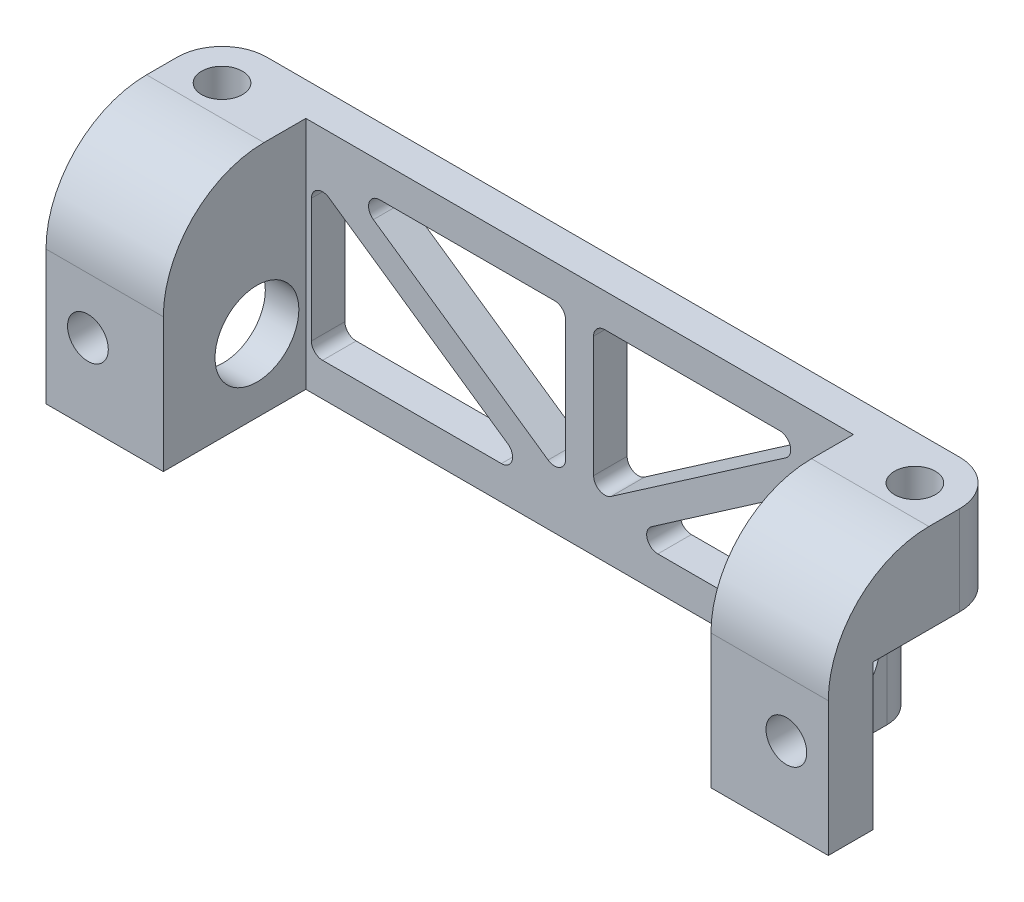
SolidWorks part; units mm, degrees
ref_plane "Front Plane" through (0, 0, 0) normal (0, 0, 1) x (1, 0, 0)
ref_plane "Top Plane" through (0, 0, 0) normal (0, 1, 0) x (1, 0, 0)
ref_plane "Right Plane" through (0, 0, 0) normal (1, 0, 0) x (0, 0, -1)
sketch "Sketch1" plane through (0, 0, 0) normal (0, 1, 0) x (1, 0, 0)
  line L0 (0, -12.75) -> (0, 12.75) construction
  line L1 (-24.5, -12.75) -> (24.5, -12.75)
  line L2 (-24.5, -12.75) -> (-24.5, 12.75)
  line L3 (-24.5, 12.75) -> (24.5, 12.75)
  line L4 (24.5, -12.75) -> (24.5, 12.75)
  line L5 (-24.5, -12.75) -> (24.5, 12.75) construction
  line L6 (-24.5, 12.75) -> (24.5, -12.75) construction
  line L7 (0, 12.75) -> (0, 15.75)
  line L9 (0, 15.75) -> (-27.5, 15.75)
  line L10 (0, 15.75) -> (0, 12.75)
  line L11 (0, 12.75) -> (-27.5, 12.75)
  line L12 (-27.5, 15.75) -> (-27.5, 12.75)
  line L13 (-24.5, 12.75) -> (-27.5, 12.75)
  line L14 (-24.5, 12.75) -> (-24.5, 0)
  line L15 (-24.5, 0) -> (-27.5, 0)
  line L16 (-27.5, 12.75) -> (-27.5, 0)
  line L17 (-27.5, 0) -> (-35, 0)
  line L18 (-27.5, 0) -> (-27.5, 3)
  line L19 (-27.5, 3) -> (-35, 3)
  line L20 (-35, 0) -> (-35, 3)
  line L21 (-35, 3) -> (-27.5, 3)
  line L22 (-35, 3) -> (-35, 15.75)
  line L23 (-35, 15.75) -> (-27.5, 15.75)
  line L24 (-27.5, 3) -> (-27.5, 15.75)
  point P0 (0, 0)
  dimension "D1" = 49
  dimension "D2" = 25.5
  dimension "D3" = 3
  dimension "D4" = 27.5
  dimension "D5" = 12.75
  dimension "D6" = 7.5
  dimension "D7" = 3
extrude "Boss-Extrude1" add sketch "Sketch1" along normal blind 21
sketch "Sketch2" plane through (0, 0, 0) normal (0, 0, 1) x (1, 0, 0)
  line L0 (-27.5, 0) -> (-27.5, 21) construction
  line L1 (-24.5, 0) -> (-35, 0) construction
  line L2 (-24.5, 21) -> (-35, 21) construction
  line L3 (-24.5, 21) -> (-24.5, 0) construction
  line L4 (-27.5, 14) -> (-35, 14)
  line L5 (-35, 21) -> (-35, 0) construction
  line L6 (-35, 14) -> (-27.5, 0) construction
  line L7 (-27.5, 0) -> (-35, 0) construction
  line L8 (-35, 0) -> (-27.5, 14) construction
  circle A0 centre (-31.25, 7) radius 1.825
  dimension "D3" = 3.65
  dimension "D1" = 3
  dimension "D2" = 7
extrude "Cut-Extrude1" cut sketch "Sketch2" against normal blind 4 contours A0
sketch "Sketch3" plane through (0, 0, 0) normal (0, -1, 0) x (1, 0, 0)
  line L0 (-24.5, 0) -> (-24.5, -12.75) construction
  line L1 (-35, -15.75) -> (-27.5, -15.75)
  line L2 (-35, -15.75) -> (-35, -4)
  line L3 (-35, -4) -> (-27.5, -4)
  line L4 (-27.5, -15.75) -> (-27.5, -4)
  line L5 (-24.5, 0) -> (-35, 0) construction
  dimension "D1" = 3
  dimension "D2" = 4
extrude "Cut-Extrude2" cut sketch "Sketch3" against normal blind 13
fillet "Fillet1" radius 4 1 edges at (-35, 17, -15.75)
sketch "Sketch5" plane through (0, 13, 0) normal (0, -1, 0) x (1, 0, 0)
  line L0 (-35, -11.75) -> (-27.5, -11.75) construction
  line L1 (-27.5, -15.75) -> (-27.5, -4) construction
  line L2 (-31, -15.75) -> (-31, -4) construction
  line L3 (-27.5, -4) -> (-35, -4) construction
  circle A0 centre (-31, -11.75) radius 1.825
  dimension "D1" = 3.65
extrude "Cut-Extrude3" cut sketch "Sketch5" against normal through all
mirror "Mirror1" about plane through (0, 21, 0) normal (-1, 0, 0) of "Cut-Extrude3", "Fillet1", "Cut-Extrude1", "Cut-Extrude2", "Boss-Extrude1"
ref_plane "Plane1" through (0, 0, -15.75) normal (0, 0, -1) x (-1, 0, 0)
sketch "Sketch10" plane through (0, 0, -15.75) normal (0, 0, -1) x (-1, 0, 0)
  line L0 (-27.5, 0) -> (27.5, 0) construction
  line L1 (-31, 21) -> (31, 21) construction
  line L2 (-27.5, 13) -> (-27.5, 0) construction
  line L3 (-24, 3) -> (-3.7939, 3)
  line L4 (-24, 3) -> (-24, 16.9699)
  line L5 (-21.0939, 18) -> (-1.25, 18)
  line L7 (-21.0939, 18) -> (-1.25, 4.2806)
  line L11 (-1.25, 4.2806) -> (-1.25, 18)
  line L14 (0, 0) -> (0, -5.962) construction
  line L16 (-24, 16.9699) -> (-3.7939, 3)
  line L17 (24, 3) -> (24, 16.9699)
  line L18 (24, 16.9699) -> (3.7939, 3)
  line L19 (24, 3) -> (3.7939, 3)
  line L20 (21.0939, 18) -> (1.25, 4.2806)
  line L21 (21.0939, 18) -> (1.25, 18)
  line L22 (1.25, 4.2806) -> (1.25, 18)
  point P5 (0, 10.5)
  point P6 (-12.5701, 10.5832)
  point P12 (0, 10.5)
  dimension "D1" = 3
  dimension "D2" = 3.5
  dimension "D3" = 4.2806
  dimension "D4" = 3
  dimension "D5" = 2.5
  dimension "D6" = 26.25
  dimension "D7" = 6.4061
extrude "Cut-Extrude5" cut sketch "Sketch10" against normal through all
fillet "Fillet2" radius 1 12 edges at (1.25, 4.2806, -14.25) (-1.25, 4.2806, -14.25) (-1.25, 18, -14.25) (-24, 16.9699, -14.25) (-24, 3, -14.25) (24, 3, -14.25) (24, 16.9699, -14.25) (3.7939, 3, -14.25) (-3.7939, 3, -14.25) (-21.0939, 18, -14.25) (1.25, 18, -14.25) (21.0939, 18, -14.25)
fillet "Fillet3" radius 9 2 edges at (29.75, 21, 0) (-29.75, 21, 0)
fillet "Fillet4" radius 3 2 edges at (27.5, 6.5, -15.75) (-27.5, 6.5, -15.75)
sketch "Sketch11" plane through (27.5, 0, 0) normal (1, 0, 0) x (0, 0, -1)
  line L0 (12.75, 0) -> (4, 13) construction
  circle A0 centre (8.375, 6.5) radius 3.75
  dimension "D1" = 7.5
extrude "Cut-Extrude6" cut sketch "Sketch11" against normal through all
